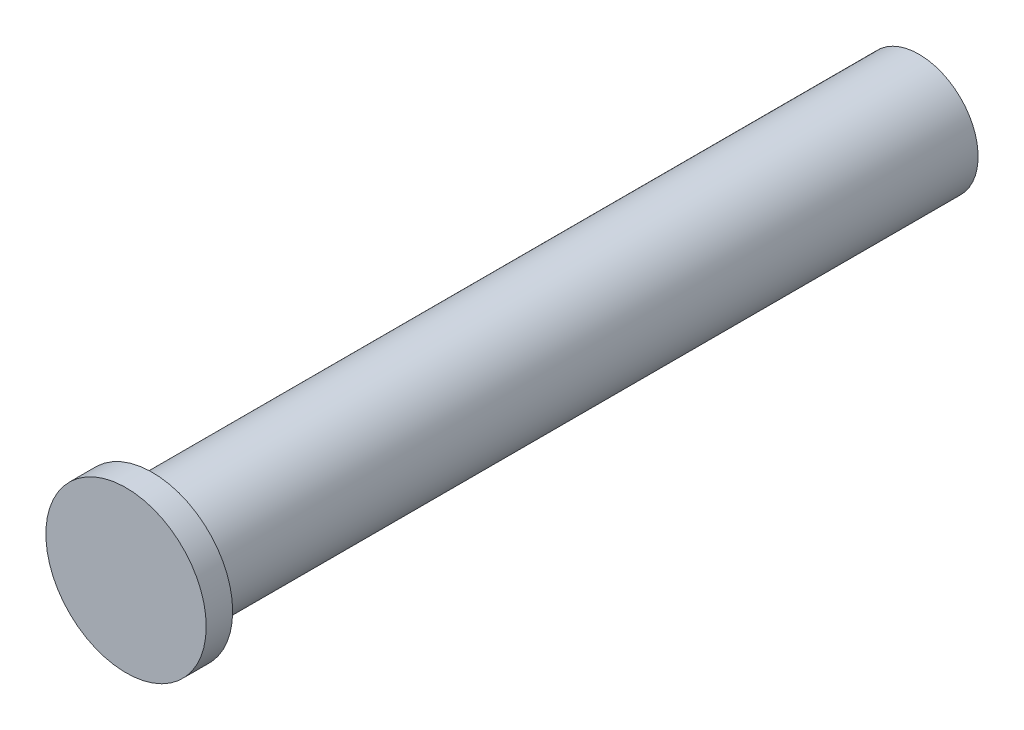
SolidWorks part; units mm, degrees
ref_plane "Plano frontal" through (0, 0, 0) normal (0, 0, 1) x (1, 0, 0)
ref_plane "Plano superior" through (0, 0, 0) normal (0, 1, 0) x (1, 0, 0)
ref_plane "Plano direito" through (0, 0, 0) normal (1, 0, 0) x (0, 0, -1)
sketch "Esboço1" plane through (0, 0, 0) normal (0, 0, 1) x (1, 0, 0)
  circle A0 centre (0, 0) radius 9.1
  dimension "D1" = 18.2
extrude "Ressalto-extrusão1" add sketch "Esboço1" against normal blind 3
sketch "Esboço2" plane through (0, 0, -3) normal (0, 0, -1) x (-1, 0, 0)
  circle A0 centre (0, 0) radius 6.7
  dimension "D1" = 13.4
extrude "Ressalto-extrusão2" add sketch "Esboço2" along normal blind 87
sketch "Esboço3" plane through (0, 0, -90) normal (0, 0, -1) x (-1, 0, 0)
  line L0 (0, 0) -> (0, 11.2026) construction
  line L1 (0, 0) -> (9.7017, -5.6013) construction
  line L2 (0, 0) -> (-9.7017, -5.6013) construction
  point P0 (0, 3)
  point P8 (2.5981, -1.5)
  point P9 (-2.5981, -1.5)
  point P10 (0, 0)
  point P14 (0, 0)
  dimension "D2" = 3
  dimension "D1" = 3
  dimension "D3" = 3
hole_wizard "Furo roscado de M21" positions "Esboço4" profile "Esboço5" tap size "M2" standard "ISO"
sketch "Esboço4" plane through (0, 0, -90) normal (0, 0, -1) x (-1, 0, 0)
  point P0 (-2.5981, -1.5)
  point P3 (0, 3)
  point P6 (2.5981, -1.5)
sketch "Esboço5" plane through (2.5981, -1.5, -90) normal (1, 0, 0) x (0, 1, 0)
  line L0 (0, 0) -> (0, 10.4807)
  line L1 (0, 10.4807) -> (0.8, 10)
  line L2 (0.8, 10) -> (0.8, 0)
  line L5 (0.8, 0) -> (0, 0)
  line L10 (0, 10.4807) -> (-0.8, 10) construction
  line L11 (0, -6.35) -> (0, 107.95) construction
  dimension "Tap Drill Dia." = 1.6
  dimension "Tap Drill Depth" = 10
  dimension "Drill Angle" = 118
cosmetic thread "Rosca de furo1"
cosmetic thread "Rosca de furo2"
cosmetic thread "Rosca de furo3"
